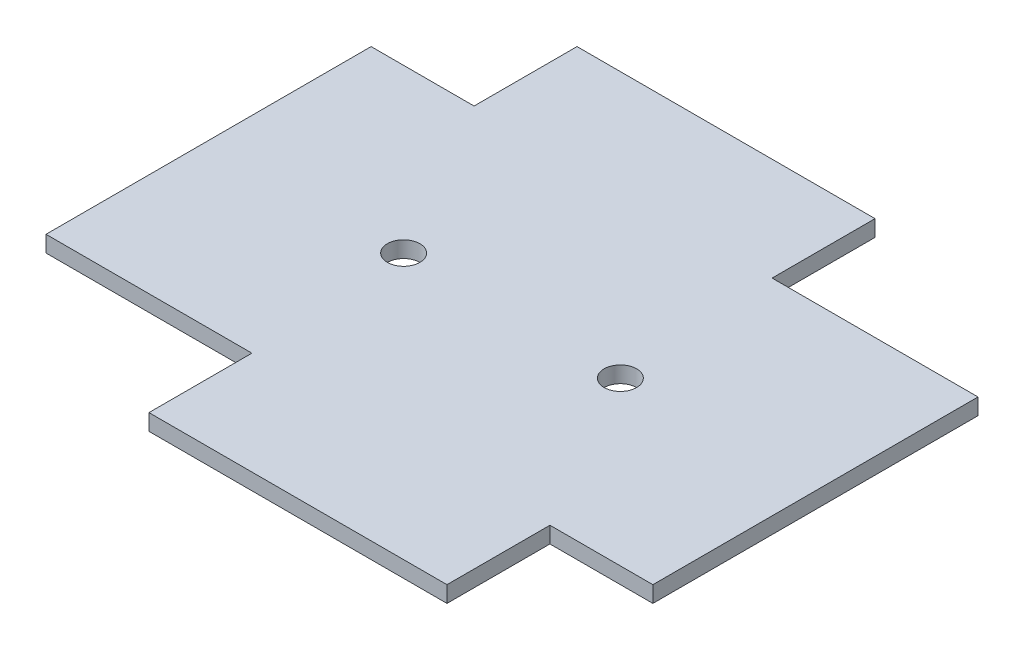
SolidWorks part; units mm, degrees
ref_plane "Front" through (0, 0, 0) normal (0, 0, 1) x (1, 0, 0)
ref_plane "Top" through (0, 0, 0) normal (0, 1, 0) x (1, 0, 0)
ref_plane "Right" through (0, 0, 0) normal (1, 0, 0) x (0, 0, -1)
sketch "Эскиз1" plane through (0, 0, 0) normal (0, 1, 0) x (1, 0, 0)
  line L0 (-28, 15) -> (-28, -15)
  line L1 (-28, -15) -> (-9, -15)
  line L2 (-9, -15) -> (-9, -24.5)
  line L3 (-9, -24.5) -> (18.5, -24.5)
  line L4 (18.5, -24.5) -> (18.5, -15)
  line L5 (18.5, -15) -> (28, -15)
  line L6 (28, -15) -> (28, 15)
  line L7 (28, 15) -> (9, 15)
  line L8 (9, 15) -> (9, 24.5)
  line L9 (9, 24.5) -> (-18.5, 24.5)
  line L10 (-18.5, 24.5) -> (-18.5, 15)
  line L11 (-18.5, 15) -> (-28, 15)
  line L12 (-10, 0) -> (10, 0) construction
  circle A0 centre (-10, 0) radius 1.5
  circle A1 centre (10, 0) radius 1.5
  point P14 (0, 0)
  point P17 (0, 0)
  dimension "D5" = 3
  dimension "D1" = 27.5
  dimension "D2" = 30
  dimension "D3" = 9.5
  dimension "D4" = 20
  dimension "D6" = 18
  dimension "D7" = 18
  dimension "D8" = 24.5
extrude "Бобышка-Вытянуть1" add sketch "Эскиз1" along normal blind 1.5
